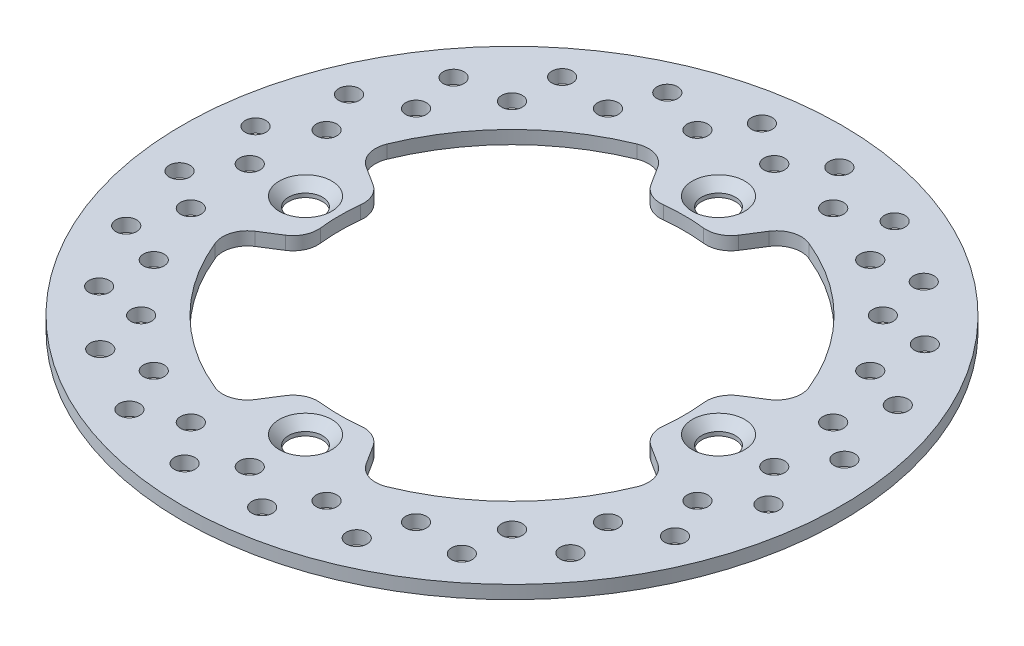
SolidWorks part; units mm, degrees
material "High-leaded brass, UNS C34200"
ref_plane "Front Plane" through (0, 0, 0) normal (0, 0, 1) x (1, 0, 0)
ref_plane "Top Plane" through (0, 0, 0) normal (0, 1, 0) x (1, 0, 0)
ref_plane "Right Plane" through (0, 0, 0) normal (1, 0, 0) x (0, 0, -1)
sketch "Sketch1" plane through (0, 0, 0) normal (0, 1, 0) x (1, 0, 0)
  line L0 (-101.346, 0) -> (101.346, 0) construction
  line L1 (0, 101.346) -> (0, -101.346) construction
  line L2 (-13.4811, 56.2213) -> (-17.0733, 61.8977)
  line L3 (13.4811, 56.2213) -> (17.0733, 61.8977)
  line L4 (56.2213, 13.4811) -> (61.8977, 17.0733)
  line L5 (56.2213, -13.4811) -> (61.8977, -17.0733)
  line L6 (13.4811, -56.2213) -> (17.0733, -61.8977)
  line L7 (-13.4811, -56.2213) -> (-17.0733, -61.8977)
  line L8 (-56.2213, -13.4811) -> (-61.8977, -17.0733)
  line L9 (-56.2213, 13.4811) -> (-61.8977, 17.0733)
  circle A0 centre (0, 0) radius 101.346
  arc A1 (6.1582, 52.7276) -> (-6.1582, 52.7276) centre (0, 0) ccw
  circle A2 centre (0, 63.5) radius 5.207
  arc A3 (-26.3825, 64.8817) -> (-64.8817, 26.3825) centre (0, 0) ccw
  arc A4 (26.3825, 64.8817) -> (17.0733, 61.8977) centre (23.5123, 57.8229) ccw
  arc A5 (13.4811, 56.2213) -> (6.1582, 52.7276) centre (7.0421, 60.2962) cw
  arc A6 (-6.1582, 52.7276) -> (-13.4811, 56.2213) centre (-7.0421, 60.2962) cw
  arc A7 (-17.0733, 61.8977) -> (-26.3825, 64.8817) centre (-23.5123, 57.8229) ccw
  arc A8 (61.8977, 17.0733) -> (64.8817, 26.3825) centre (57.8229, 23.5123) ccw
  arc A9 (52.7276, 6.1582) -> (56.2213, 13.4811) centre (60.2962, 7.0421) cw
  arc A10 (52.7276, -6.1582) -> (52.7276, 6.1582) centre (0, 0) ccw
  arc A11 (56.2213, -13.4811) -> (52.7276, -6.1582) centre (60.2962, -7.0421) cw
  arc A12 (64.8817, -26.3825) -> (61.8977, -17.0733) centre (57.8229, -23.5123) ccw
  circle A13 centre (63.5, 0) radius 5.207
  arc A14 (17.0733, -61.8977) -> (26.3825, -64.8817) centre (23.5123, -57.8229) ccw
  arc A15 (6.1582, -52.7276) -> (13.4811, -56.2213) centre (7.0421, -60.2962) cw
  arc A16 (-6.1582, -52.7276) -> (6.1582, -52.7276) centre (0, 0) ccw
  arc A17 (-13.4811, -56.2213) -> (-6.1582, -52.7276) centre (-7.0421, -60.2962) cw
  arc A18 (-26.3825, -64.8817) -> (-17.0733, -61.8977) centre (-23.5123, -57.8229) ccw
  circle A19 centre (0, -63.5) radius 5.207
  arc A20 (-61.8977, -17.0733) -> (-64.8817, -26.3825) centre (-57.8229, -23.5123) ccw
  arc A21 (-52.7276, -6.1582) -> (-56.2213, -13.4811) centre (-60.2962, -7.0421) cw
  arc A22 (-52.7276, 6.1582) -> (-52.7276, -6.1582) centre (0, 0) ccw
  arc A23 (-56.2213, 13.4811) -> (-52.7276, 6.1582) centre (-60.2962, 7.0421) cw
  arc A24 (-64.8817, 26.3825) -> (-61.8977, 17.0733) centre (-57.8229, 23.5123) ccw
  circle A25 centre (-63.5, 0) radius 5.207
  arc A26 (-64.8817, -26.3825) -> (-26.3825, -64.8817) centre (0, 0) ccw
  arc A27 (26.3825, -64.8817) -> (64.8817, -26.3825) centre (0, 0) ccw
  arc A28 (64.8817, 26.3825) -> (26.3825, 64.8817) centre (0, 0) ccw
  point P15 (20.32, 67.0281)
  point P18 (10.795, 51.9768)
  point P21 (-10.795, 51.9768)
  point P24 (-20.32, 67.0281)
  point P70 (0, 0)
  dimension "D2" = 106.172
  dimension "D3" = 10.414
  dimension "D4" = 202.692
  dimension "D5" = 140.081
  dimension "D8" = 7.62
  dimension "D1" = 127
  dimension "D6" = 40.64
  dimension "D7" = 21.59
  dimension "D9" = 4
extrude "Boss-Extrude1" add sketch "Sketch1" along normal blind 4.064 contours A0 A28 A8 L4 A9 A10 A11 L5 A12 A27 A14 L6 A15 A16 A17 L7 A18 A26 A20 L8 A21 A22 A23 L9 A24 A3 A7 L2 A6 A1 A5 L3 A4 A25 A19 A13 A2
hole_wizard "CSK for #0 Flat Head Machine Screw (100)1" positions "Sketch3" profile "Sketch4" countersink size "#0" standard "ANSI Inch" end condition through all
sketch "Sketch3" plane through (0, 4.064, 0) normal (0, 1, 0) x (1, 0, 0)
  point P0 (0, 63.5)
  point P3 (63.5, 0)
  point P6 (0, -63.5)
  point P9 (-63.5, 0)
sketch "Sketch4" plane through (0, 4.064, -63.5) normal (1, 0, 0) x (0, 0, 1)
  line L0 (0, 0) -> (0, 4.064)
  line L1 (0, 4.064) -> (5.08, 4.064)
  line L2 (5.08, 4.064) -> (5.08, 2.9845)
  line L3 (5.08, 2.9845) -> (8.0645, 0)
  line L5 (8.0645, 0) -> (0, 0)
  line L6 (-5.08, 2.9845) -> (-8.0645, 0) construction
  line L11 (0, -6.35) -> (0, 107.95) construction
  dimension "Thru Hole Dia." = 10.16
  dimension "Thru Hole Depth" = 4.064
  dimension "Near C'Sink Dia." = 16.129
  dimension "Near C'Sink Angle" = 90
sketch "Sketch5" plane through (0, 4.064, 0) normal (0, 1, 0) x (1, 0, 0)
  circle A0 centre (80.645, 0) radius 3.175
  circle A1 centre (89.535, 12.7) radius 3.175
  circle A2 centre (63.5, 0) radius 5.207 construction
  dimension "D1" = 6.35
  dimension "D5" = 6.35
  dimension "D2" = 17.145
  dimension "D3" = 8.89
  dimension "D4" = 12.7
extrude "Cut-Extrude1" cut sketch "Sketch5" against normal through all
pattern_circular "CirPattern1" count 24 over 360 about axis through (0, 0, 0) along (0, 1, 0) of "Cut-Extrude1"
